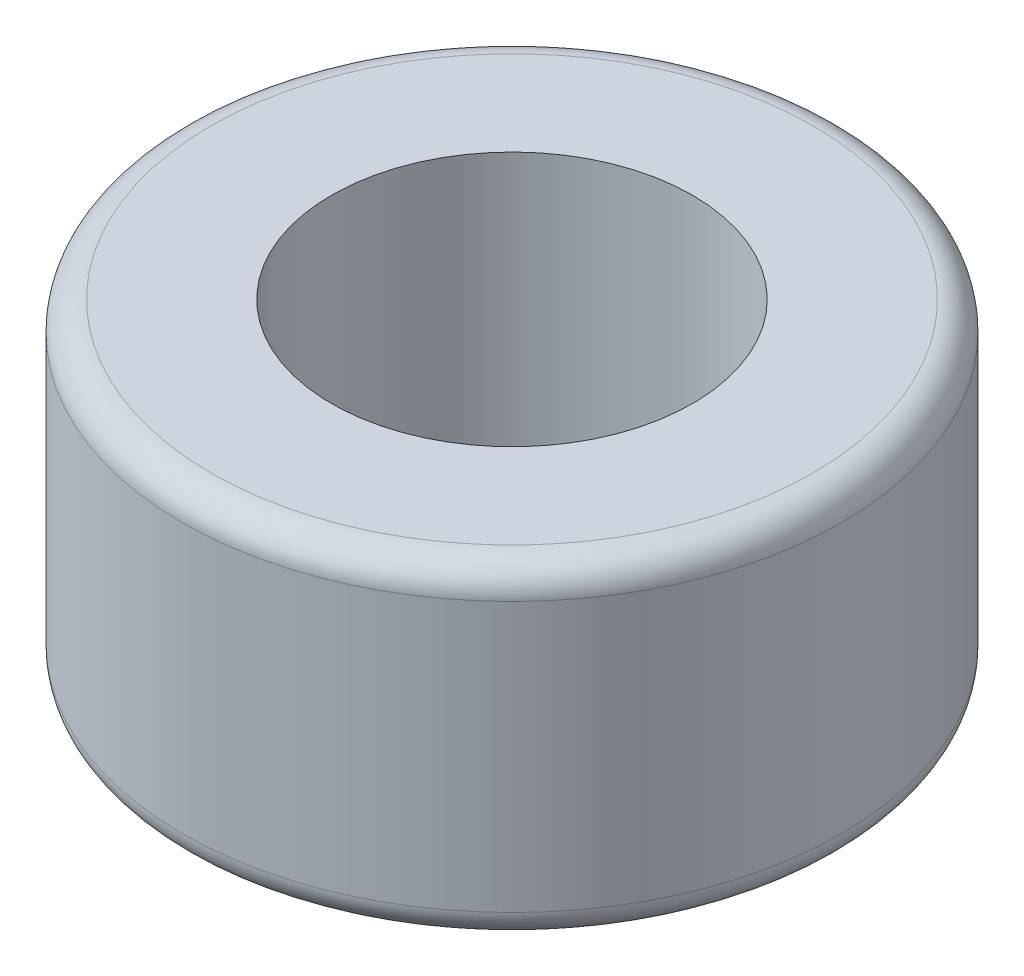
SolidWorks part; units mm, degrees
material "AISI 316 Stainless Steel Sheet (SS)"
ref_plane "Front Plane" through (0, 0, 0) normal (0, 0, 1) x (1, 0, 0)
ref_plane "Top Plane" through (0, 0, 0) normal (0, 1, 0) x (1, 0, 0)
ref_plane "Right Plane" through (0, 0, 0) normal (1, 0, 0) x (0, 0, -1)
sketch "Sketch1" plane through (0, 0, 0) normal (0, 0, 1) x (1, 0, 0)
  line L0 (0, 0) -> (0, 6.9426) construction
  line L1 (-5.75, 2.85) -> (-3.15, 2.85)
  line L2 (-5.75, 2.85) -> (-5.75, -2.85)
  line L3 (-5.75, -2.85) -> (-3.15, -2.85)
  line L4 (-3.15, 2.85) -> (-3.15, -2.85)
  point P4 (-3.15, 0)
  dimension "D1" = 5.75
  dimension "D2" = 3.15
  dimension "D3" = 5.7
revolve "Revolve1" add sketch "Sketch1" angle 360 about L0
fillet "Fillet1" radius 0.5 2 edges at (0, -2.85, -5.75) (0, 2.85, -5.75)
